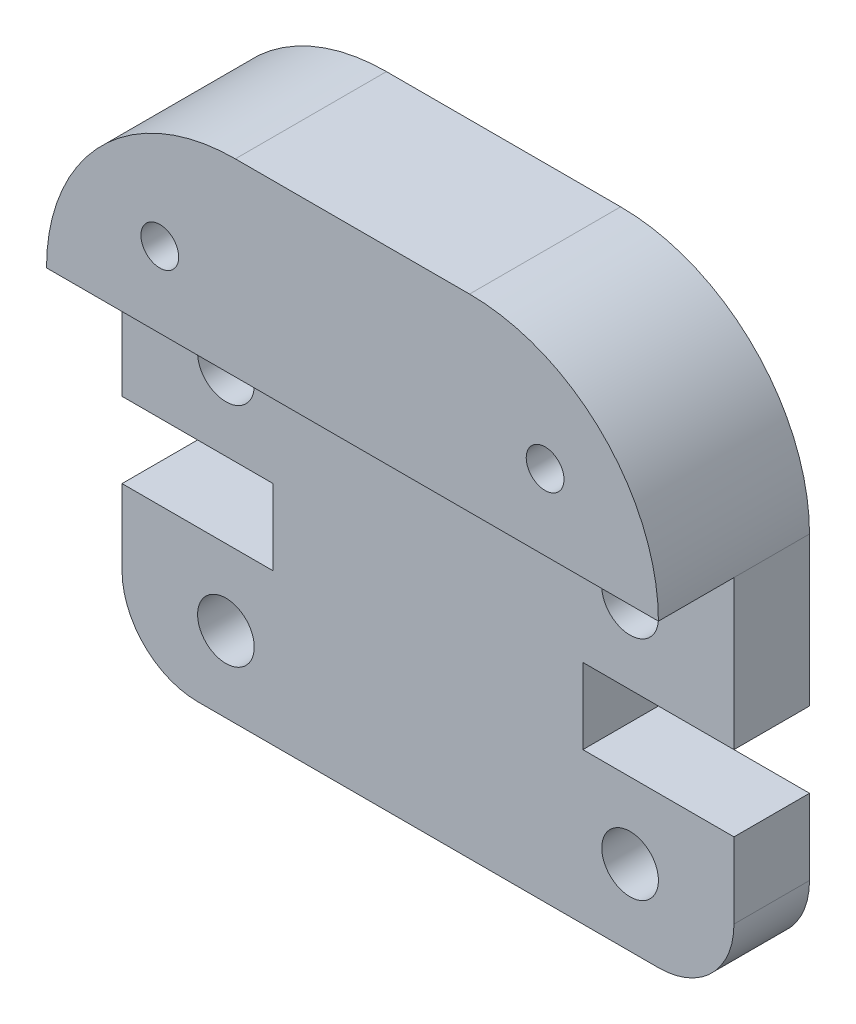
SolidWorks part; units mm, degrees
ref_plane "Front Plane" through (0, 0, 0) normal (0, 0, 1) x (1, 0, 0)
ref_plane "Top Plane" through (0, 0, 0) normal (0, 1, 0) x (1, 0, 0)
ref_plane "Right Plane" through (0, 0, 0) normal (1, 0, 0) x (0, 0, -1)
sketch "Sketch2" plane through (0, 0, 0) normal (0, 0, 1) x (1, 0, 0)
  line L0 (0, 9.945) -> (0, 6)
  line L1 (5, 14.945) -> (11.2, 14.945)
  line L2 (8.1, 14.945) -> (8.1, 0) construction
  line L3 (2, 0) -> (14.2, 0)
  line L4 (12.2, 4) -> (16.2, 4)
  line L5 (12.2, 6) -> (12.2, 4)
  line L6 (16.2, 6) -> (12.2, 6)
  line L7 (16.2, 2) -> (16.2, 4)
  line L8 (16.2, 9.945) -> (16.2, 6)
  line L17 (0, 2) -> (0, 4)
  line L18 (0, 6) -> (4, 6)
  line L20 (4, 6) -> (4, 4)
  line L21 (4, 4) -> (0, 4)
  circle A0 centre (13.45, 8) radius 0.75
  circle A1 centre (13.45, 2) radius 0.75
  arc A2 (16.2, 2) -> (14.2, 0) centre (14.2, 2) cw
  circle A3 centre (13.2, 11.942) radius 0.5
  arc A4 (11.2, 14.945) -> (16.2, 9.945) centre (11.2, 9.945) cw
  arc A11 (5, 14.945) -> (0, 9.945) centre (5, 9.945) ccw
  circle A13 centre (3, 11.942) radius 0.5
  arc A15 (0, 2) -> (2, 0) centre (2, 2) ccw
  circle A17 centre (2.75, 2) radius 0.75
  circle A18 centre (2.75, 8) radius 0.75
  dimension "D1" = 1
  dimension "D2" = 1.5
  dimension "D3" = 5
  dimension "D4" = 2
  dimension "D5" = 3
  dimension "D6" = 8.1
  dimension "D7" = 8
  dimension "D8" = 3.003
  dimension "D9" = 14.945
extrude "Boss-Extrude1" add sketch "Sketch2" along normal blind 4
sketch "Sketch3" plane through (0, 0, 4) normal (0, 0, -1) x (-1, 0, 0)
  line L0 (-16.2, 9.945) -> (0, 9.945)
  line L1 (0, 9.945) -> (0, 0)
  line L2 (0, 0) -> (-16.2, 0)
  line L3 (-16.2, 0) -> (-16.2, 9.945)
extrude "Cut-Extrude2" cut sketch "Sketch3" along normal blind 2
equation "\"D6@Sketch2\"= \"fingerWidth@parametersSketch@prostheticParameters.SLDPRT\" / 2'Finger width"
equation "\"D9@Sketch2\"= ( ( \"HL@parametersSketch@prostheticParameters.SLDPRT\" * 0.097 ) - 3 ) 'DIP legth-Silicone Sheet DIP"
